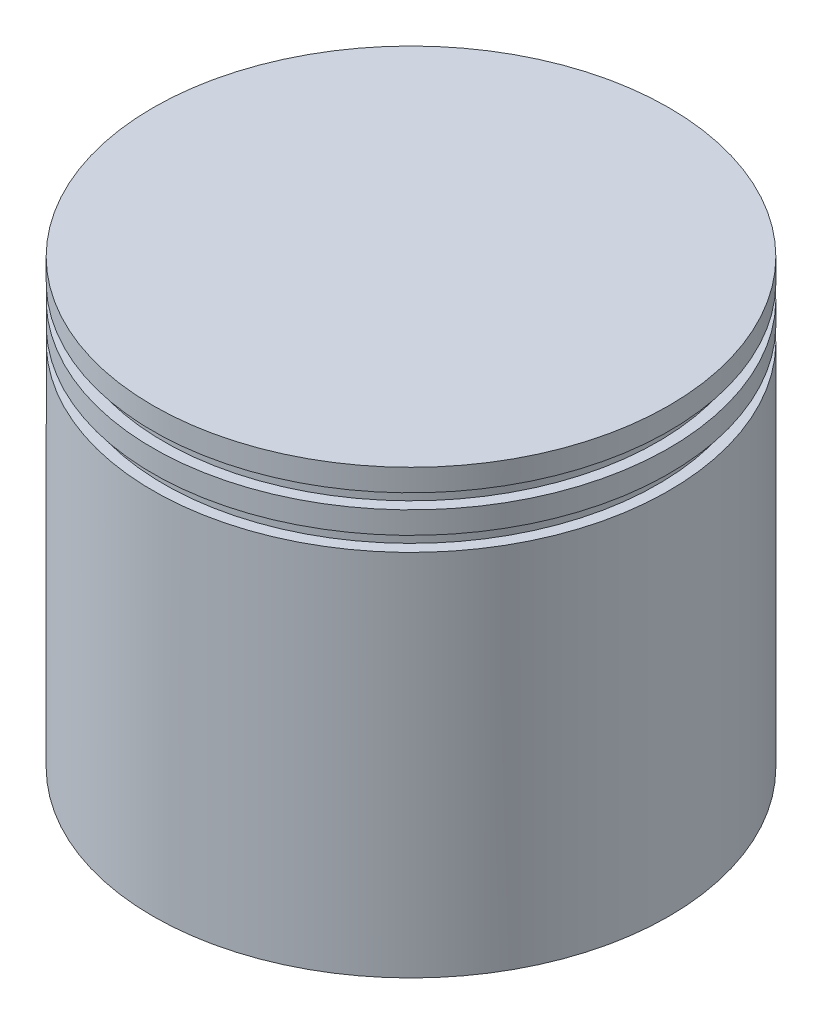
SolidWorks part; units mm, degrees
ref_plane "前视" through (0, 0, 0) normal (0, 0, 1) x (1, 0, 0)
ref_plane "上视" through (0, 0, 0) normal (0, 1, 0) x (1, 0, 0)
ref_plane "右视" through (0, 0, 0) normal (1, 0, 0) x (0, 0, -1)
sketch "草图1" plane through (0, 0, 0) normal (0, 1, 0) x (1, 0, 0)
  circle A0 centre (0, 0) radius 35
extrude "拉伸1" add sketch "草图1" along normal blind 60
shell "抽壳1" thickness 3
sketch "草图2" plane through (0, 0, 0) normal (1, 0, 0) x (0, 0, -1)
  line L0 (-35, 0) -> (35, 0) construction
  circle A0 centre (0, 15) radius 3
  dimension "D1" = 15
extrude "拉伸2" add sketch "草图2" against normal blind 8
sketch "草图3" plane through (-8, 0, 0) normal (-1, 0, 0) x (0, 0, 1)
  circle A0 centre (0, 15) radius 6
extrude "拉伸3" add sketch "草图3" along normal up to body draft 8 draft outward yes
mirror "镜向1" about plane through (0, 15, 0) normal (1, 0, 0) of "拉伸2", "拉伸3"
sketch "草图4" plane through (0, 0, 0) normal (0, 0, 1) x (1, 0, 0)
  line L0 (-33.5, 57) -> (-35, 57)
  line L1 (-35, 60) -> (-35, 0) construction
  line L2 (-35, 57) -> (-35, 55)
  line L3 (-35, 55) -> (-33.5, 55)
  line L4 (-33.5, 57) -> (-33.5, 55)
  line L5 (-33.5, 52) -> (-35, 52)
  line L6 (-35, 52) -> (-35, 50)
  line L7 (-35, 50) -> (-33.5, 50)
  line L8 (-33.5, 50) -> (-33.5, 52)
  line L9 (0, 47.5422) -> (0, 61.3033) construction
  line L10 (35, 60) -> (-35, 60) construction
  dimension "D1" = 1.5
  dimension "D2" = 1.5
  dimension "D3" = 3
  dimension "D4" = 2
  dimension "D5" = 3
  dimension "D6" = 2
revolve "切除-旋转1" cut sketch "草图4" angle 360 about L9
